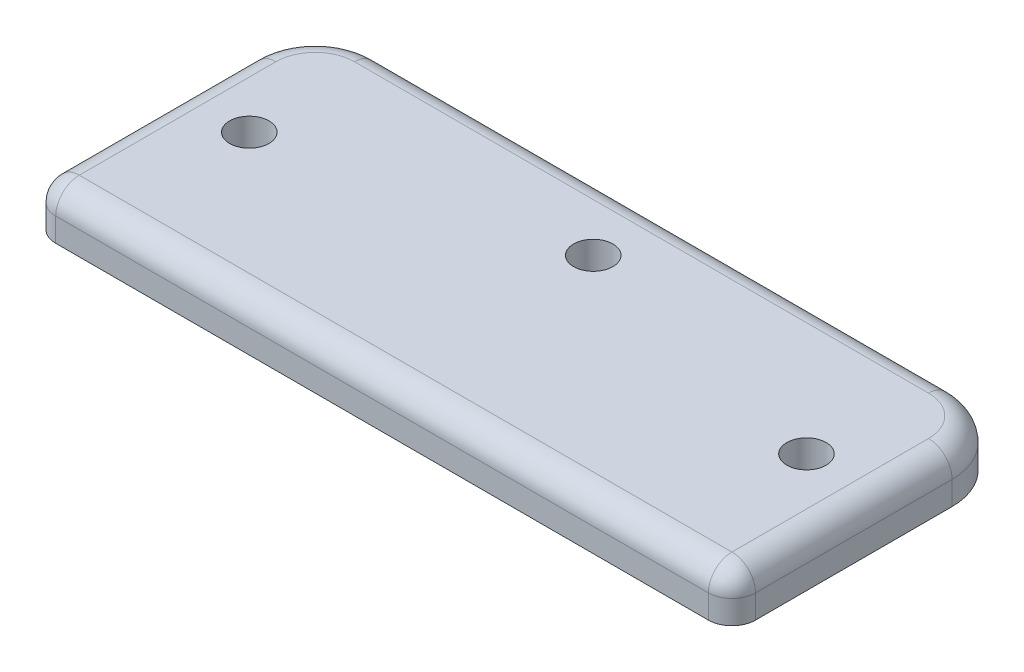
SolidWorks part; units mm, degrees
ref_plane "Front Plane" through (0, 0, 0) normal (0, 0, 1) x (1, 0, 0)
ref_plane "Top Plane" through (0, 0, 0) normal (0, 1, 0) x (1, 0, 0)
ref_plane "Right Plane" through (0, 0, 0) normal (1, 0, 0) x (0, 0, -1)
sketch "Sketch1" plane through (0, 0, 0) normal (0, 1, 0) x (1, 0, 0)
  line L1 (-36.5, 18) -> (36.5, 18)
  line L2 (-44.5, 10) -> (-44.5, -15)
  line L3 (-41.5, -18) -> (41.5, -18)
  line L4 (44.5, 10) -> (44.5, -15)
  line L5 (-44.5, 18) -> (44.5, -18) construction
  line L6 (-44.5, -18) -> (44.5, 18) construction
  circle A1 centre (0, 8.86) radius 2.5
  circle A2 centre (35.43, 0.55) radius 2.5
  circle A3 centre (-35.43, 0.55) radius 2.5
  arc A4 (44.5, 10) -> (36.5, 18) centre (36.5, 10) ccw
  arc A5 (-36.5, 18) -> (-44.5, 10) centre (-36.5, 10) ccw
  arc A6 (41.5, -18) -> (44.5, -15) centre (41.5, -15) ccw
  arc A7 (-41.5, -18) -> (-44.5, -15) centre (-41.5, -15) cw
  point P0 (0, 0)
  dimension "D1" = 8
  dimension "D2" = 3
extrude "Boss-Extrude1" add sketch "Sketch1" along normal blind 6
fillet "Fillet1" radius 3 8 edges at (42.1569, 6, -15.6569) (44.5, 6, 2.5) (43.6213, 6, 17.1213) (0, 6, 18) (-43.6213, 6, 17.1213) (-44.5, 6, 2.5) (-42.1569, 6, -15.6569) (0, 6, -18)
